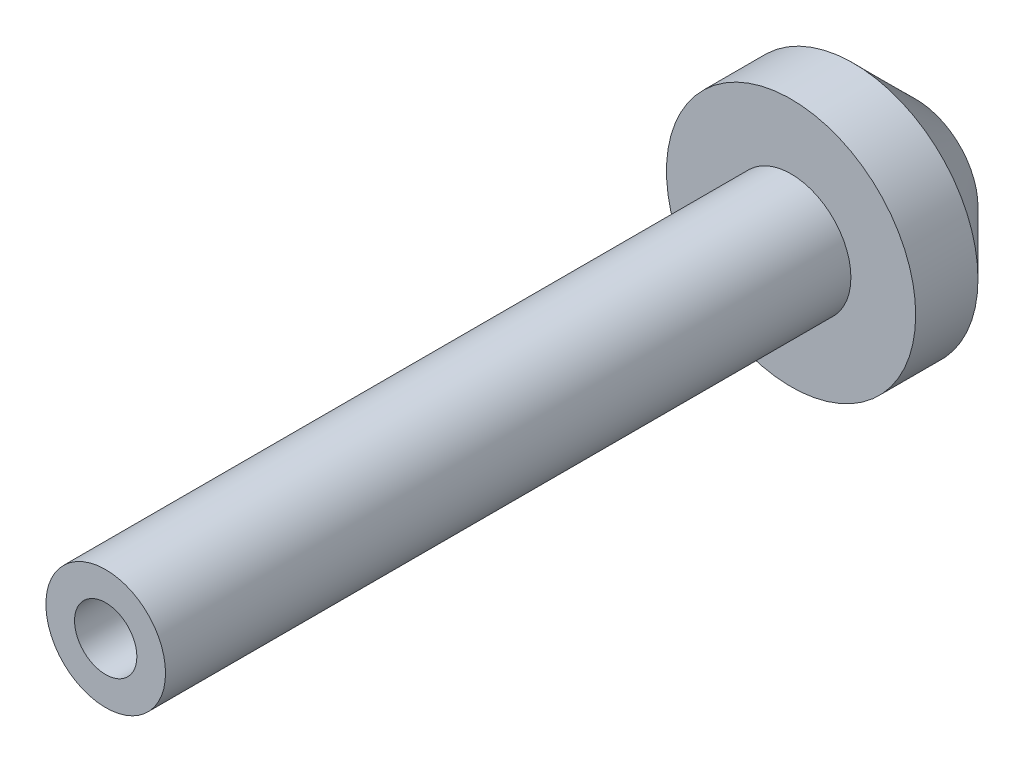
SolidWorks part; units mm, degrees
ref_plane "前视基准面" through (0, 0, 0) normal (0, 0, 1) x (1, 0, 0)
ref_plane "上视基准面" through (0, 0, 0) normal (0, 1, 0) x (1, 0, 0)
ref_plane "右视基准面" through (0, 0, 0) normal (1, 0, 0) x (0, 0, -1)
other "Configuration Table"
sketch "Sketch1" plane through (0, 0, 0) normal (0, 0, 1) x (1, 0, 0)
  circle A0 centre (0, 0) radius 5
  dimension "D1" = 10
extrude "Boss-Extrude1" add sketch "Sketch1" along normal blind 5
sketch "Sketch2" plane through (0, 0, 5) normal (0, 0, 1) x (1, 0, 0)
  circle A0 centre (0, 0) radius 2.4
  dimension "D1" = 4.8
extrude "Boss-Extrude2" add sketch "Sketch2" along normal blind 27.5
chamfer "Chamfer1" distance 2.5 angle 45 1 edges at (5, 0, 0)
sketch "Sketch3" plane through (0, 0, 32.5) normal (0, 0, 1) x (1, 0, 0)
  circle A0 centre (0, 0) radius 1.25
  dimension "D1" = 2.5
extrude "Cut-Extrude1" cut sketch "Sketch3" against normal through all
